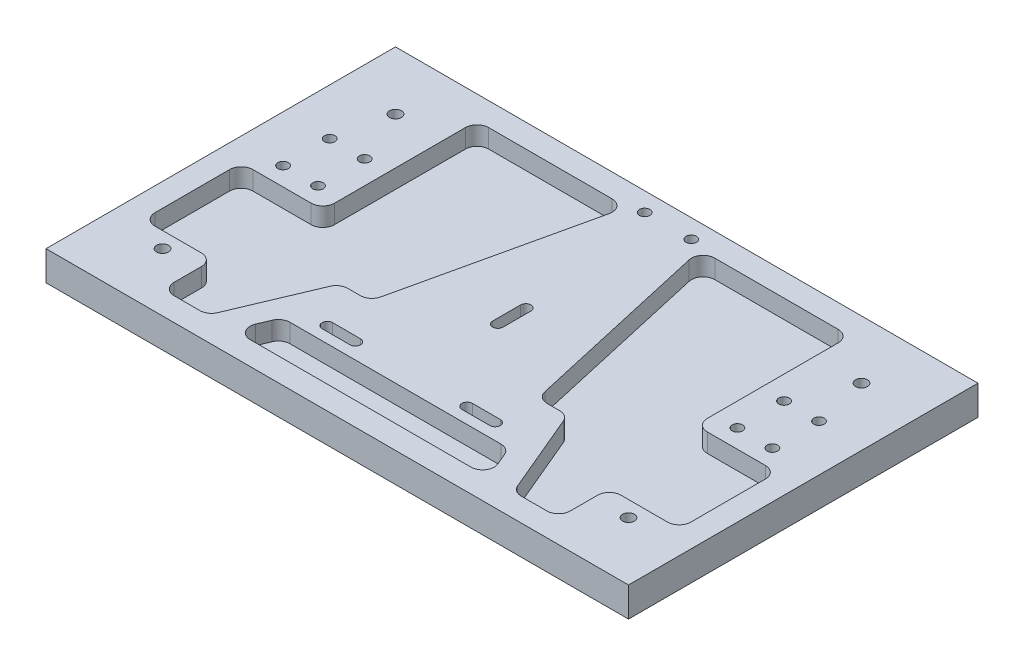
SolidWorks part; units mm, degrees
material "1060 Alloy"
ref_plane "Front Plane" through (0, 0, 0) normal (0, 0, 1) x (1, 0, 0)
ref_plane "Top Plane" through (0, 0, 0) normal (0, 1, 0) x (1, 0, 0)
ref_plane "Right Plane" through (0, 0, 0) normal (1, 0, 0) x (0, 0, -1)
sketch "Sketch1" plane through (0, 0, 0) normal (0, 1, 0) x (1, 0, 0)
  line L1 (125, 75) -> (-125, 75)
  line L2 (125, 75) -> (125, -75)
  line L3 (125, -75) -> (-125, -75)
  line L4 (-125, 75) -> (-125, -75)
  line L5 (125, 75) -> (-125, -75) construction
  line L6 (125, -75) -> (-125, 75) construction
  point P0 (0, 0)
  dimension "D1" = 150
  dimension "D2" = 250
extrude "Boss-Extrude1" add sketch "Sketch1" along normal blind 12.7
sketch "Sketch5" plane through (0, 0, 0) normal (0, 1, 0) x (1, 0, 0)
  line L22 (-125, -75) -> (125, -75) construction
  line L24 (30, -43.25) -> (-30, -43.25) construction
  line L30 (0, -43.25) -> (0, 0) construction
  line L32 (-90, 26.75) -> (-105, 26.75) construction
  line L33 (-90, 26.75) -> (-90, 6.75) construction
  line L34 (-90, 6.75) -> (-105, 6.75) construction
  line L35 (-105, 26.75) -> (-105, 6.75) construction
  line L36 (-90, 16.75) -> (-44.634, 16.75) construction
  line L38 (-125, 75) -> (-125, -75) construction
  line L39 (10, 66.93) -> (-10, 66.93) construction
  line L41 (0, 66.93) -> (0, -0.07) construction
  point P26 (-30, -43.25)
  point P28 (30, -43.25)
  point P111 (0, -0.07)
  point P115 (-105, 26.75)
  point P117 (-90, 26.75)
  point P119 (-90, 6.75)
  point P121 (-105, 6.75)
  point P167 (-10, 66.93)
  point P169 (10, 66.93)
  dimension "D1" = 60
  dimension "D2" = 43.18
  dimension "D3" = 31.75
  dimension "D4" = 60
  dimension "D5" = 20
  dimension "D6" = 15
  dimension "D7" = 20
  dimension "D8" = 67
  dimension "D9" = 20
hole_wizard "CBORE for #8 Binding Head Machine Screw1" positions "Sketch5" profile "Sketch6" counterbore size "#8" standard "ANSI Inch" end condition through all
sketch "Sketch6" plane through (-30, 0, 43.25) normal (1, 0, 0) x (0, 0, -1)
  line L0 (0, 0) -> (0, 12.7)
  line L1 (0, 12.7) -> (2.2479, 12.7)
  line L3 (2.2479, 12.7) -> (2.2479, 4.445)
  line L4 (2.2479, 4.445) -> (4.7625, 4.445)
  line L5 (4.7625, 4.445) -> (4.7625, 0)
  line L7 (4.7625, 0) -> (0, 0)
  line L11 (0, -6.35) -> (0, 107.95) construction
  dimension "Thru Hole Dia." = 4.4958
  dimension "Thru Hole Depth" = 12.7
  dimension "C'Bore Dia." = 9.525
  dimension "C'Bore Depth" = 4.445
sketch "Sketch8" plane through (0, 0, 0) normal (0, 1, 0) x (1, 0, 0)
  line L4 (-100, 50) -> (100, 50) construction
  line L5 (-100, 50) -> (-100, -50) construction
  line L6 (-100, -50) -> (100, -50) construction
  line L7 (100, 50) -> (100, -50) construction
  line L8 (-100, 50) -> (100, -50) construction
  line L9 (-100, -50) -> (100, 50) construction
  line L10 (125, -75) -> (125, 75) construction
  line L11 (125, 75) -> (-125, 75) construction
  point P1 (100, 50)
  point P12 (60.9595, -22.8595)
  point P15 (0, 0)
  point P60 (-100, 50)
  point P63 (-100, -50)
  point P66 (100, -50)
  dimension "D1" = 25
  dimension "D2" = 25
hole_wizard "1/4-20 Tapped Hole1" positions "Sketch8" profile "Sketch9" tap size "1/4-20" standard "ANSI Inch"
sketch "Sketch9" plane through (100, 0, -50) normal (1, 0, 0) x (0, 0, -1)
  line L0 (0, 0) -> (0, 12.7)
  line L1 (0, 12.7) -> (2.5527, 12.7)
  line L2 (2.5527, 12.7) -> (2.5527, 0)
  line L5 (2.5527, 0) -> (0, 0)
  line L11 (0, -6.35) -> (0, 107.95) construction
  dimension "Thru Tap Drill Dia." = 5.1054
  dimension "Thru Tap Drill Depth" = 12.7
sketch "Sketch10" plane through (0, 12.7, 0) normal (0, 1, 0) x (1, 0, 0)
  line L4 (-80, 65) -> (-80, -1.2)
  line L5 (-80, -1.2) -> (-115, -1.2)
  line L6 (-115, -1.2) -> (-115, -43.25)
  line L7 (-115, -43.25) -> (-85, -43.25)
  line L8 (-85, -43.25) -> (-85, -65)
  line L9 (-85, -65) -> (-65.6551, -65)
  line L10 (-65.6551, -65) -> (-48.8, -25)
  line L11 (-48.8, -25) -> (-36.1, -25)
  line L12 (-36.1, -25) -> (-15.78, 65)
  line L15 (-15.78, 65) -> (-80, 65)
  line L16 (125, 75) -> (-125, 75) construction
  line L17 (-125, 75) -> (-125, -75) construction
  line L18 (-125, -75) -> (125, -75) construction
  dimension "D1" = 10
  dimension "D2" = 76.2
  dimension "D3" = 10
  dimension "D4" = 10
  dimension "D5" = 31.75
  dimension "D6" = 40
  dimension "D9" = 35
  dimension "D10" = 59.3449
  dimension "D11" = 76.2
  dimension "D12" = 50
  dimension "D13" = 88.9
  dimension "D14" = 109.22
extrude "Cut-Extrude1" cut sketch "Sketch10" against normal blind 8
fillet "Fillet1" radius 5 10 edges at (-115, 8.7, 1.2) (-115, 8.7, 43.25) (-85, 8.7, 65) (-85, 8.7, 43.25) (-65.6551, 8.7, 65) (-48.8, 8.7, 25) (-36.1, 8.7, 25) (-80, 8.7, 1.2) (-15.78, 8.7, -65) (-80, 8.7, -65)
mirror "Mirror1" about plane through (0, 0, 0) normal (1, 0, 0) of "Cut-Extrude1", "Fillet1"
sketch "Sketch14" plane through (0, 12.7, 0) normal (0, 1, 0) x (1, 0, 0)
  line L0 (-54.9056, -65) -> (54.9056, -65)
  line L1 (54.9056, -65) -> (48.5849, -50)
  line L2 (48.5849, -50) -> (-48.5849, -50)
  line L3 (-48.5849, -50) -> (-54.9056, -65)
  line L4 (-64.3664, -61.9416) -> (-50.0888, -28.0584) construction
  line L5 (64.3664, -61.9416) -> (50.0888, -28.0584) construction
  line L8 (-64.3664, -61.9416) -> (-50.0888, -28.0584) construction
  line L9 (-125, -75) -> (125, -75) construction
  dimension "D1" = 9.906
  dimension "D2" = 9.906
  dimension "D3" = 25
extrude "Cut-Extrude3" cut sketch "Sketch14" against normal blind 8
fillet "Fillet3" radius 5 4 edges at (-48.5849, 8.7, 50) (48.5849, 8.7, 50) (54.9056, 8.7, 65) (-54.9056, 8.7, 65)
sketch "Sketch15" plane through (0, 12.7, 0) normal (0, 1, 0) x (1, 0, 0)
  line L0 (-36, -43.25) -> (-24, -43.25) construction
  line L1 (-36, -41.0021) -> (-24, -41.0021)
  line L2 (-36, -45.4979) -> (-24, -45.4979)
  line L3 (24, -43.25) -> (36, -43.25) construction
  line L4 (24, -41.0021) -> (36, -41.0021)
  line L5 (24, -45.4979) -> (36, -45.4979)
  line L6 (0, 5.93) -> (0, -6.07) construction
  line L7 (2.2479, 5.93) -> (2.2479, -6.07)
  line L8 (-2.2479, 5.93) -> (-2.2479, -6.07)
  arc A0 (-36, -41.0021) -> (-36, -45.4979) centre (-36, -43.25) ccw
  arc A1 (-24, -45.4979) -> (-24, -41.0021) centre (-24, -43.25) ccw
  arc A2 (24, -41.0021) -> (24, -45.4979) centre (24, -43.25) ccw
  arc A3 (36, -45.4979) -> (36, -41.0021) centre (36, -43.25) ccw
  arc A4 (2.2479, 5.93) -> (-2.2479, 5.93) centre (0, 5.93) ccw
  arc A5 (-2.2479, -6.07) -> (2.2479, -6.07) centre (0, -6.07) ccw
  circle A6 centre (0, -0.07) radius 2.2479 construction
  circle A7 centre (30, -43.25) radius 2.2479 construction
  circle A8 centre (-30, -43.25) radius 2.2479 construction
  point P2 (-30, -43.25)
  point P9 (30, -43.25)
  point P17 (0, -0.07)
  dimension "D1" = 12
  dimension "D2" = 12
  dimension "D3" = 12
extrude "Cut-Extrude4" cut sketch "Sketch15" against normal through all
sketch "Sketch16" plane through (0, 0, 0) normal (0, -1, 0) x (1, 0, 0)
  line L0 (0, -6) -> (0, 6) construction
  line L1 (-4.7625, -6) -> (-4.7625, 6)
  line L2 (4.7625, -6) -> (4.7625, 6)
  line L3 (36, 43.25) -> (24, 43.25) construction
  line L4 (36, 38.4875) -> (24, 38.4875)
  line L5 (36, 48.0125) -> (24, 48.0125)
  line L6 (-24, 43.25) -> (-36, 43.25) construction
  line L7 (-24, 38.4875) -> (-36, 38.4875)
  line L8 (-24, 48.0125) -> (-36, 48.0125)
  arc A0 (-4.7625, -6) -> (4.7625, -6) centre (0, -6) ccw
  arc A1 (4.7625, 6) -> (-4.7625, 6) centre (0, 6) ccw
  arc A2 (36, 38.4875) -> (36, 48.0125) centre (36, 43.25) ccw
  arc A3 (24, 48.0125) -> (24, 38.4875) centre (24, 43.25) ccw
  arc A4 (-24, 38.4875) -> (-24, 48.0125) centre (-24, 43.25) ccw
  arc A5 (-36, 48.0125) -> (-36, 38.4875) centre (-36, 43.25) ccw
  arc A6 (-34.1986, 41.0021) -> (-25.8014, 41.0021) centre (-30, 43.25) ccw construction
  arc A7 (25.8014, 41.0021) -> (34.1986, 41.0021) centre (30, 43.25) ccw construction
  arc A8 (-2.2479, 4.2686) -> (-2.2479, -4.1286) centre (0, 0.07) ccw construction
  point P2 (0, 0)
  point P9 (30, 43.25)
  point P17 (-30, 43.25)
  dimension "D1" = 12
  dimension "D2" = 12
  dimension "D3" = 12
extrude "Cut-Extrude5" cut sketch "Sketch16" against normal up to surface (4.445 mm away) up to face at (-3.5052, 4.445, 0.07)
mirror "Mirror3" about plane through (0, 0, 0) normal (1, 0, 0) of "CBORE for #8 Binding Head Machine Screw1"
